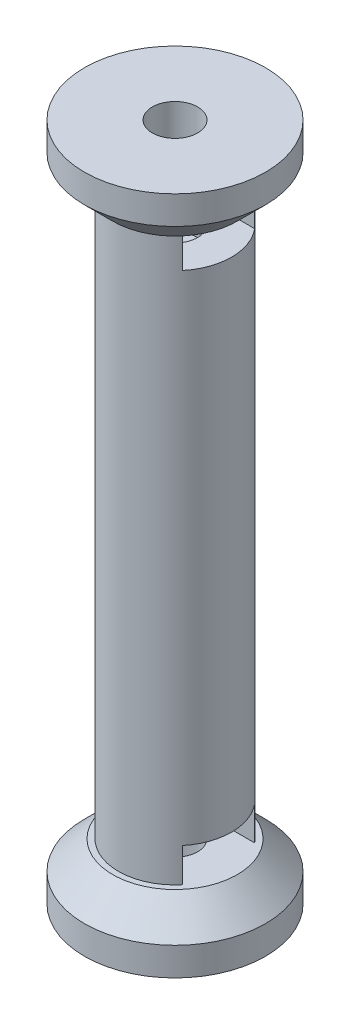
SolidWorks part; units mm, degrees
ref_plane "Front Plane" through (0, 0, 0) normal (0, 0, 1) x (1, 0, 0)
ref_plane "Top Plane" through (0, 0, 0) normal (0, 1, 0) x (1, 0, 0)
ref_plane "Right Plane" through (0, 0, 0) normal (1, 0, 0) x (0, 0, -1)
sketch "Sketch1" plane through (0, 0, 0) normal (0, 1, 0) x (1, 0, 0)
  circle A0 centre (0, 0) radius 5
  dimension "D1" = 10
extrude "Boss-Extrude1" add sketch "Sketch1" along normal mid plane 50 contours A0
sketch "Sketch2" plane through (0, 25, 0) normal (0, 1, 0) x (1, 0, 0)
  circle A0 centre (0, 0) radius 8
  dimension "D1" = 16
extrude "Boss-Extrude2" add sketch "Sketch2" along normal blind 5 contours A0
ref_plane "Plane3" through (0, -25, 0) normal (0, -1, 0) x (-1, 0, 0)
ref_plane "Plane5" through (0, 25, 0) normal (0, -1, 0) x (-1, 0, 0)
ref_plane "Plane6" through (0, 0, 0) normal (0, -1, 0) x (-1, 0, 0)
chamfer "Chamfer2" distance 2.5 angle 45 1 edges at (0, 25, 8)
sketch "Sketch3" plane through (0, 30, 0) normal (0, 1, 0) x (1, 0, 0)
  circle A0 centre (0, 0) radius 2
  dimension "D1" = 4
extrude "Cut-Extrude1" cut sketch "Sketch3" against normal blind 10 contours A0
sketch "Sketch6" plane through (0, 25, 0) normal (0, -1, 0) x (-1, 0, 0)
  line L5 (3.5, 3.2) -> (-11.1436, 3.2)
  line L6 (3.5, 3.2) -> (3.5, -3.2)
  line L7 (3.5, -3.2) -> (-11.1436, -3.2)
  line L8 (-11.1436, 3.2) -> (-11.1436, -3.2)
  circle A0 centre (0, 0) radius 2 construction
  circle A1 centre (0, 0) radius 2 construction
  point P4 (3.5, 0)
  point P5 (0, 3.2)
  point P8 (8.9251, 3.3264)
  point P9 (4.9488, 3.2441)
  dimension "D1" = 6.4
  dimension "D2" = 14.6436
  dimension "D3" = 3.5
extrude "Cut-Extrude2" cut sketch "Sketch6" along normal blind 3
chamfer "Chamfer4" distance 1 angle 45 2 edges at (-3.5, 23.5, 3.2) (-3.5, 23.5, -3.2)
mirror "Mirror4" about plane through (0, 0, 0) normal (0, -1, 0) of "Chamfer2", "Boss-Extrude2", "Cut-Extrude2", "Chamfer4", "Cut-Extrude1"
